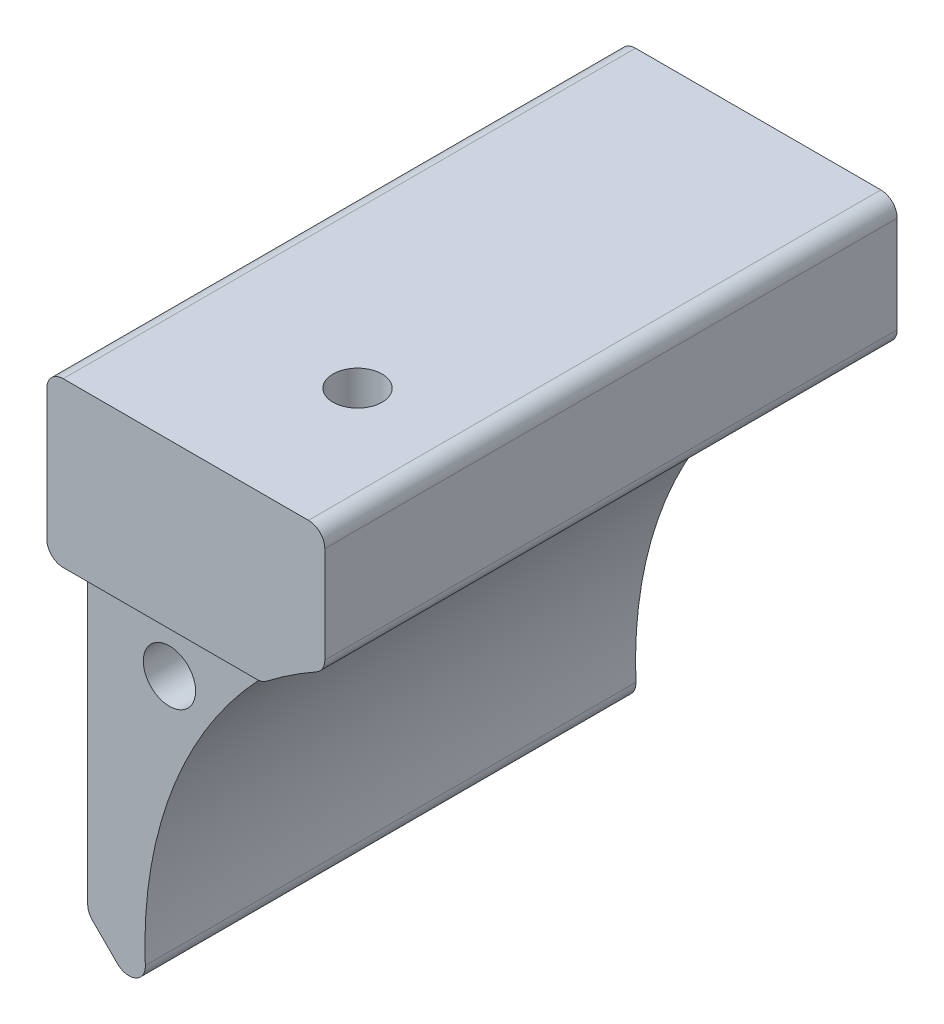
SolidWorks part; units mm, degrees
ref_plane "Front Plane" through (0, 0, 0) normal (0, 0, 1) x (1, 0, 0)
ref_plane "Top Plane" through (0, 0, 0) normal (0, 1, 0) x (1, 0, 0)
ref_plane "Right Plane" through (0, 0, 0) normal (1, 0, 0) x (0, 0, -1)
sketch "Sketch1" plane through (0, 0, 0) normal (0, 0, 1) x (1, 0, 0)
  line L0 (0, 25.4) -> (0, 50.8)
  line L4 (0, 25.4) -> (4.8032, 20.5968)
  line L5 (3.7197, 21.6803) -> (21.6803, 3.7197) construction
  line L7 (0, 50.8) -> (0, 63.5)
  line L8 (0, 63.5) -> (21.59, 63.5)
  line L11 (21.59, 53.975) -> (21.59, 63.5)
  arc A0 (21.59, 53.975) -> (4.8032, 20.5968) centre (36.83, 25.4) ccw
  circle A1 centre (6.35, 44.45) radius 2.032
  point P9 (17.1655, 50.8)
  point P11 (16.7395, 50.8)
  point P14 (0, 0)
  point P15 (0, 0)
  dimension "D3" = 64.77
  dimension "D4" = 50.8
  dimension "D1" = 25.4
  dimension "D2" = 36.83
  dimension "D5" = 12.7
  dimension "D6" = 21.59
extrude "Boss-Extrude1" add sketch "Sketch1" along normal mid plane 38.1
sketch "Sketch2" plane through (0, 0, 19.05) normal (0, 0, 1) x (1, 0, 0)
  line L1 (0, 63.5) -> (21.59, 63.5)
  line L2 (0, 63.5) -> (0, 50.8)
  line L3 (0, 50.8) -> (16.7395, 50.8)
  line L4 (21.59, 63.5) -> (21.59, 53.975)
  arc A0 (16.7395, 50.8) -> (21.59, 53.975) centre (36.83, 25.4) cw
  arc A1 (21.59, 53.975) -> (4.8032, 20.5968) centre (36.83, 25.4) ccw construction
  point P1 (16.7395, 50.8)
  point P4 (0, 0)
  dimension "D1" = 50.8
extrude "Boss-Extrude2" add sketch "Sketch2" along normal blind 3.175
mirror "Mirror1" about plane through (0, 0, 0) normal (0, 0, 1) of "Boss-Extrude2"
fillet "Fillet1" radius 1.27 9 edges at (4.8032, 20.5968, 0) (21.59, 63.5, 0) (0, 63.5, 0) (0, 25.4, 0) (0, 50.8, -20.6375) (16.7395, 50.8, -20.6375) (0, 50.8, 20.6375) (21.59, 53.975, 0) (16.7395, 50.8, 20.6375)
sketch "Sketch3" plane through (0, 63.5, 0) normal (0, 1, 0) x (1, 0, 0)
  line L0 (20.32, -22.225) -> (1.27, -22.225) construction
  circle A0 centre (13.335, -11.43) radius 1.905
  dimension "D1" = 10.795
  dimension "D3" = 3.81
  dimension "D2" = 13.335
extrude "Cut-Extrude1" cut sketch "Sketch3" against normal through all
